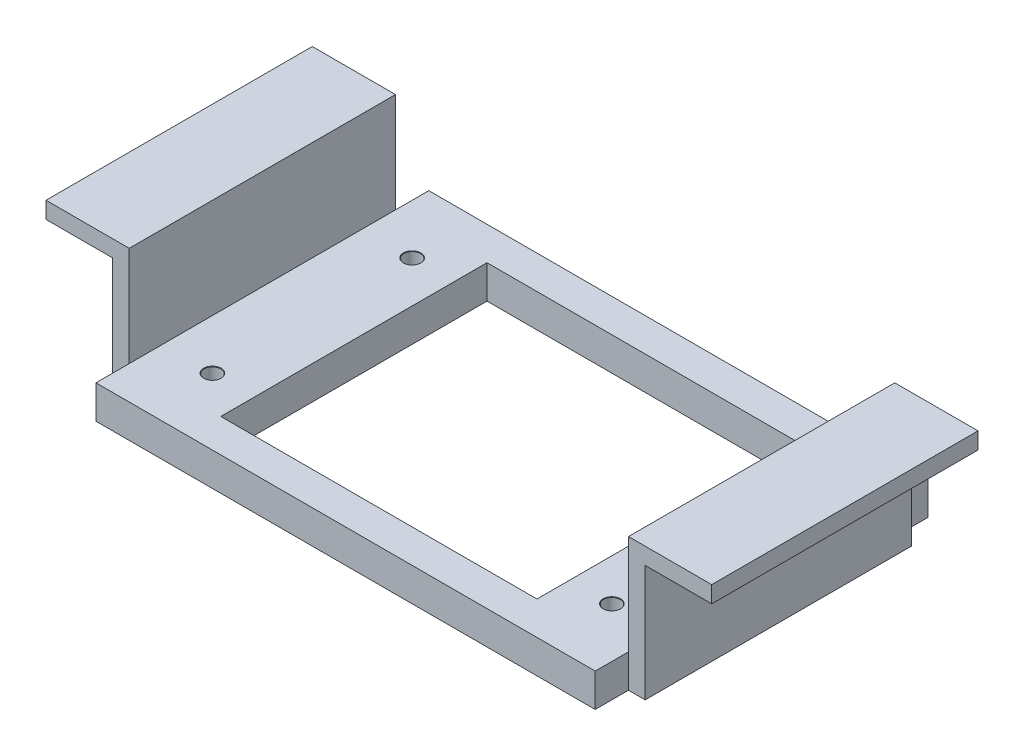
SolidWorks part; units mm, degrees
ref_plane "前视基准面" through (0, 0, 0) normal (0, 0, 1) x (1, 0, 0)
ref_plane "上视基准面" through (0, 0, 0) normal (0, 1, 0) x (1, 0, 0)
ref_plane "右视基准面" through (0, 0, 0) normal (1, 0, 0) x (0, 0, -1)
sketch "草图1" plane through (0, 0, 0) normal (0, 1, 0) x (1, 0, 0)
  line L1 (16, -8) -> (-16, -8)
  line L2 (16, -8) -> (16, 8)
  line L3 (16, 8) -> (-16, 8)
  line L4 (-16, -8) -> (-16, 8)
  line L5 (16, -8) -> (-16, 8) construction
  line L6 (16, 8) -> (-16, -8) construction
  point P0 (0, 0)
  dimension "D1" = 32
  dimension "D2" = 16
extrude "凸台-拉伸1" add sketch "草图1" along normal blind 2
sketch "草图2" plane through (0, 2, 0) normal (0, 1, 0) x (1, 0, 0)
  line L0 (-16, -8) -> (16, -8) construction
  line L1 (-16, 8) -> (-15, 8)
  line L2 (-16, 8) -> (-16, -8)
  line L3 (-16, -8) -> (-15, -8)
  line L4 (-15, 8) -> (-15, -8)
  dimension "D1" = 1
extrude "凸台-拉伸2" add sketch "草图2" along normal blind 6
sketch "草图3" plane through (0, 2, 0) normal (0, 1, 0) x (1, 0, 0)
  line L0 (-15, -8) -> (16, -8) construction
  line L1 (16, 8) -> (15, 8)
  line L2 (16, 8) -> (16, -8)
  line L3 (16, -8) -> (15, -8)
  line L4 (15, 8) -> (15, -8)
  dimension "D1" = 1
extrude "凸台-拉伸3" add sketch "草图3" along normal blind 6
sketch "草图4" plane through (-16, 0, 0) normal (-1, 0, 0) x (0, 0, 1)
  line L0 (8, 8) -> (8, 0) construction
  line L1 (-8, 8) -> (8, 8)
  line L2 (-8, 8) -> (-8, 7)
  line L3 (-8, 7) -> (8, 7)
  line L4 (8, 8) -> (8, 7)
  dimension "D1" = 1
extrude "凸台-拉伸4" add sketch "草图4" along normal blind 4
sketch "草图5" plane through (16, 0, 0) normal (1, 0, 0) x (0, 0, -1)
  line L0 (8, 8) -> (8, 0) construction
  line L1 (-8, 8) -> (8, 8)
  line L2 (-8, 8) -> (-8, 7)
  line L3 (-8, 7) -> (8, 7)
  line L4 (8, 8) -> (8, 7)
  dimension "D1" = 1
extrude "凸台-拉伸5" add sketch "草图5" along normal blind 4
hole_wizard "Ø1.0 (1) 直径孔1" positions "草图11" profile "草图12" hole size "Ø1.0" standard "GB" end condition through all
sketch "草图11" plane through (0, 2, 0) normal (0, 1, 0) x (1, 0, 0)
  line L0 (-15, 0) -> (15, 0) construction
  line L1 (-15, -8) -> (-15, 8) construction
  line L2 (15, 8) -> (15, -8) construction
  line L4 (0, 8) -> (0, -8) construction
  line L5 (15, 8) -> (-15, 8) construction
  line L6 (-15, -8) -> (15, -8) construction
  point P0 (-12, 6)
  point P2 (-12, -6)
  point P4 (12, -6)
  point P6 (12, 6)
  dimension "D1" = 12
  dimension "D2" = 12
  dimension "D3" = 12
  dimension "D4" = 12
  dimension "D5" = 6
  dimension "D6" = 6
  dimension "D7" = 6
  dimension "D8" = 6
sketch "草图12" plane through (-12, 2, -6) normal (1, 0, 0) x (0, 0, 1)
  line L0 (0, 0) -> (0, 2)
  line L1 (0, 2) -> (0.5, 2)
  line L2 (0.5, 2) -> (0.5, 0.025)
  line L3 (0.5, 0.025) -> (0.525, 0)
  line L5 (0.525, 0) -> (0, 0)
  line L6 (-0.5, 0.025) -> (-0.525, 0) construction
  line L11 (0, -6.35) -> (0, 107.95) construction
  dimension "通孔孔直径" = 1
  dimension "通孔孔深度" = 2
  dimension "近端锥形沉头孔直径" = 1.05
  dimension "近端锥形沉头孔角度" = 90
sketch "草图13" plane through (0, 2, 0) normal (0, 1, 0) x (1, 0, 0)
  line L0 (-12, 6) -> (12, 6) construction
  line L1 (12, 6) -> (12, -6) construction
  line L2 (12, -6) -> (-12, -6) construction
  line L3 (-12, -6) -> (-12, 6) construction
  line L4 (16, 8) -> (-16, 8) construction
sketch "草图14" plane through (0, 0, -8) normal (0, 0, -1) x (-1, 0, 0)
  line L0 (-16, 0) -> (16, 0) construction
  line L1 (-15, 2) -> (14.9984, 2)
  line L2 (-15, 2) -> (-15, 0)
  line L3 (-15, 0) -> (14.9984, 0)
  line L4 (14.9984, 2) -> (14.9984, 0)
extrude "凸台-拉伸6" add sketch "草图14" along normal blind 2
sketch "草图15" plane through (0, 0, 8) normal (0, 0, 1) x (1, 0, 0)
  line L0 (-16, 0) -> (16, 0) construction
  line L1 (-15, 2) -> (14.9984, 2)
  line L2 (-15, 2) -> (-15, 0)
  line L3 (-15, 0) -> (14.9984, 0)
  line L4 (14.9984, 2) -> (14.9984, 0)
extrude "凸台-拉伸7" add sketch "草图15" along normal blind 2
sketch "草图16" plane through (0, 2, 0) normal (0, 1, 0) x (1, 0, 0)
  line L1 (9.5, -8) -> (-9.5, -8)
  line L2 (9.5, -8) -> (9.5, 8)
  line L3 (9.5, 8) -> (-9.5, 8)
  line L4 (-9.5, -8) -> (-9.5, 8)
  line L5 (9.5, -8) -> (-9.5, 8) construction
  line L6 (9.5, 8) -> (-9.5, -8) construction
  point P0 (0, 0)
  dimension "D1" = 19
  dimension "D2" = 16
extrude "切除-拉伸1" cut sketch "草图16" against normal blind 2
